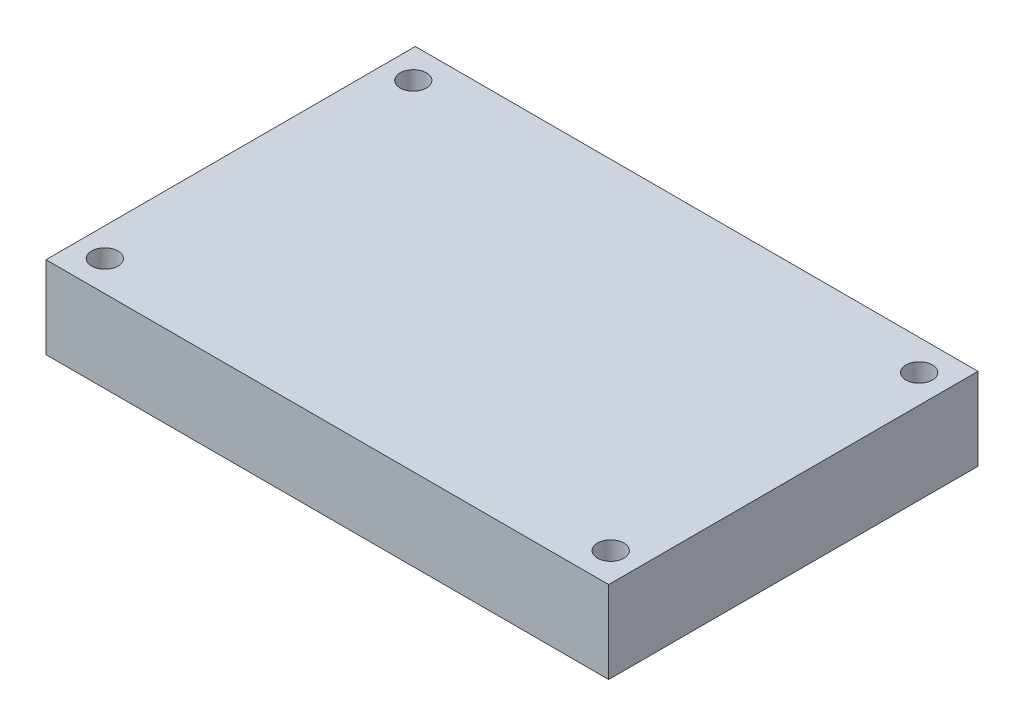
SolidWorks part; units mm, degrees
ref_plane "前视基准面" through (0, 0, 0) normal (0, 0, 1) x (1, 0, 0)
ref_plane "上视基准面" through (0, 0, 0) normal (0, 1, 0) x (1, 0, 0)
ref_plane "右视基准面" through (0, 0, 0) normal (1, 0, 0) x (0, 0, -1)
sketch "Sketch1" plane through (0, 0, 0) normal (0, 1, 0) x (1, 0, 0)
  line L1 (-34.2, 22.45) -> (34.2, 22.45)
  line L2 (-34.2, 22.45) -> (-34.2, -22.45)
  line L3 (-34.2, -22.45) -> (34.2, -22.45)
  line L4 (34.2, 22.45) -> (34.2, -22.45)
  line L5 (0, -22.45) -> (0, 22.45) construction
  line L6 (-34.2, 0) -> (34.2, 0) construction
  point P0 (0, 0)
  dimension "D1" = 68.4
  dimension "D2" = 44.9
extrude "Boss-Extrude1" add sketch "Sketch1" along normal blind 10
sketch "Sketch2" plane through (0, 0, 0) normal (0, 1, 0) x (1, 0, 0)
  line L1 (-30.75, 18.75) -> (30.75, 18.75) construction
  line L2 (-30.75, 18.75) -> (-30.75, -18.75) construction
  line L3 (-30.75, -18.75) -> (30.75, -18.75) construction
  line L4 (30.75, 18.75) -> (30.75, -18.75) construction
  line L5 (0, -18.75) -> (0, 18.75) construction
  line L6 (-30.75, 0) -> (30.75, 0) construction
  circle A0 centre (30.75, 18.75) radius 1.6
  circle A1 centre (30.75, -18.75) radius 1.6
  circle A2 centre (-30.75, -18.75) radius 1.6
  circle A3 centre (-30.75, 18.75) radius 1.6
  point P0 (0, 0)
  dimension "D3" = 3.2
  dimension "D1" = 61.5
  dimension "D2" = 37.5
extrude "Cut-Extrude1" cut sketch "Sketch2" along normal up to next
